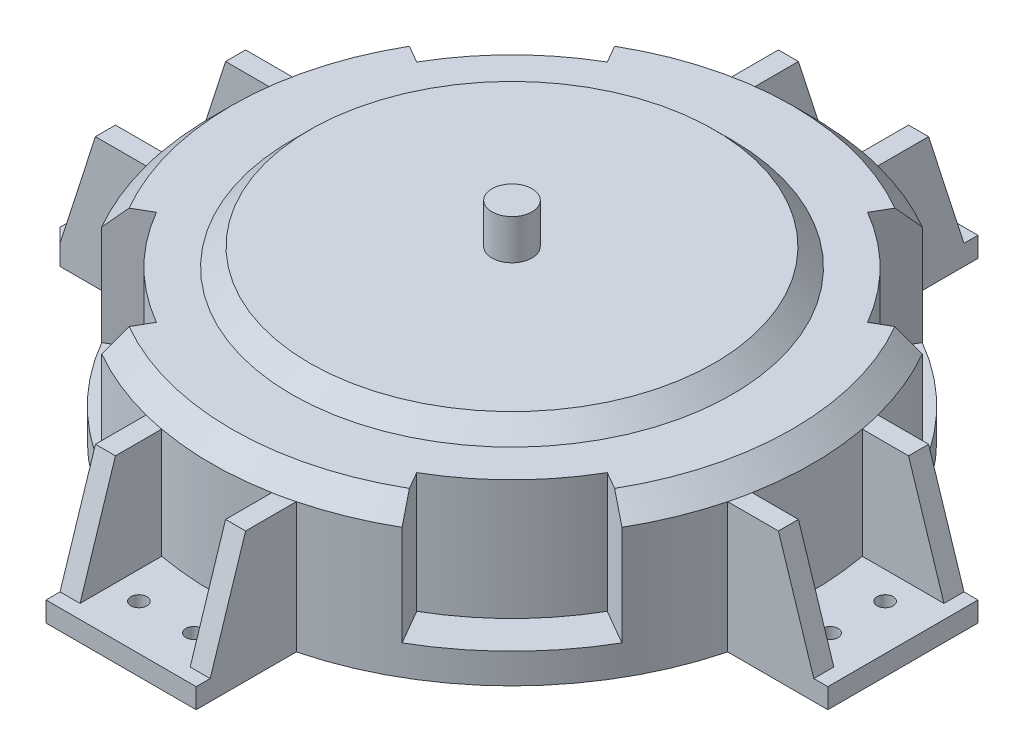
SolidWorks part; units mm, degrees
ref_plane "Front Plane" through (0, 0, 0) normal (0, 0, 1) x (1, 0, 0)
ref_plane "Top Plane" through (0, 0, 0) normal (0, 1, 0) x (1, 0, 0)
ref_plane "Right Plane" through (0, 0, 0) normal (1, 0, 0) x (0, 0, -1)
sketch "Sketch1" plane through (0, 0, 0) normal (0, 1, 0) x (1, 0, 0)
  circle A0 centre (0, 0) radius 150
  dimension "D1" = 300
extrude "Boss-Extrude1" add sketch "Sketch1" along normal blind 75
chamfer "Chamfer1" distance 10 angle 45 1 edges at (0, 75, 150)
sketch "Sketch2" plane through (0, 75, 0) normal (0, 1, 0) x (1, 0, 0)
  line L0 (-150, 0) -> (-195.2369, 0) construction
  line L1 (-195.2369, 37.5) -> (-195.2369, -37.5)
  line L2 (-195.2369, 37.5) -> (-145.2369, 37.5)
  line L3 (-195.2369, -37.5) -> (-145.2369, -37.5)
  circle A0 centre (0, 0) radius 150 construction
  arc A1 (-145.2369, 37.5) -> (-145.2369, -37.5) centre (0, 0) ccw
  point P5 (-195.2369, 0)
  dimension "D1" = 75
  dimension "D2" = 50
extrude "Boss-Extrude2" add sketch "Sketch2" along normal blind 10 from offset 75 offset against normal yes
chamfer "Chamfer2" distance 7 angle 45 2 edges at (-195.2369, 5, -37.5) (-195.2369, 5, 37.5)
sketch "Sketch3" plane through (0, 0, 37.5) normal (0, 0, 1) x (1, 0, 0)
  line L0 (-150, 65) -> (-170.5569, 65)
  line L1 (-170.5569, 65) -> (-188.2369, 10)
  line L2 (-188.2369, 10) -> (-188.2369, 0)
  line L3 (-188.2369, 0) -> (-145.2369, 0)
  line L4 (-145.2369, 0) -> (-145.2369, 65)
  line L5 (-150, 65) -> (150, 65) construction
  line L6 (-145.2369, 65) -> (-150, 65)
  dimension "D1" = 17.68
extrude "Boss-Extrude3" add sketch "Sketch3" against normal blind 10
sketch "Sketch4" plane through (0, 10, 0) normal (0, 1, 0) x (1, 0, 0)
  line L0 (-195.2369, 0) -> (-150, 0) construction
  line L1 (-195.2369, 30.5) -> (-195.2369, -30.5) construction
  line L2 (-172.6184, 0) -> (-172.6184, -27.5) construction
  line L6 (-188.2369, -27.5) -> (-147.4576, -27.5) construction
  arc A0 (-145.2369, 37.5) -> (-147.4576, -27.5) centre (0, 0) ccw construction
  arc A1 (-145.2369, -37.5) -> (-147.4576, -27.5) centre (0, 0) ccw construction
  circle A2 centre (-172.6184, -13.75) radius 4
  dimension "D1" = 8
extrude "Cut-Extrude1" cut sketch "Sketch4" against normal through all both and the other way through all
ref_plane "Plane1" through (0, 0, 0) normal (0, 0, 1) x (1, 0, 0)
mirror "Mirror1" about plane through (0, 0, 0) normal (0, 0, 1) of "Boss-Extrude3", "Cut-Extrude1"
pattern_circular "CirPattern1" count 4 over 360 about axis through (0, 0, 0) along (0, 1, 0) of "Boss-Extrude2", "Mirror1", "Boss-Extrude3", "Cut-Extrude1"
sketch "Sketch5" plane through (0, 75, 0) normal (0, 1, 0) x (1, 0, 0)
  line L0 (0, 0) -> (0, -150) construction
  line L1 (0, 0) -> (-150, 0) construction
  line L2 (-112.5833, -65) -> (-129.9038, -75)
  line L3 (-65, -112.5833) -> (-75, -129.9038)
  arc A0 (-129.9038, -75) -> (-75, -129.9038) centre (0, 0) ccw
  arc A2 (-112.5833, -65) -> (-65, -112.5833) centre (0, 0) ccw
  dimension "D1" = 30
  dimension "D2" = 30
extrude "Cut-Extrude2" cut sketch "Sketch5" against normal blind 60 and the other way through all
pattern_circular "CirPattern2" count 4 over 360 about axis through (0, 75, 0) along (0, -1, 0) of "Cut-Extrude2"
sketch "Sketch6" plane through (0, 75, 0) normal (0, 1, 0) x (1, 0, 0)
  circle A0 centre (0, 0) radius 110
  dimension "D1" = 220
extrude "Boss-Extrude4" add sketch "Sketch6" along normal blind 9 draft 45
sketch "Sketch7" plane through (0, 84, 0) normal (0, 1, 0) x (1, 0, 0)
  circle A0 centre (0, 0) radius 10
  dimension "D1" = 20
extrude "Boss-Extrude5" add sketch "Sketch7" along normal blind 20
scale "Ölçek1" bodies to scale 110 scale about centroid uniform scaling yes scale factor 0.2
